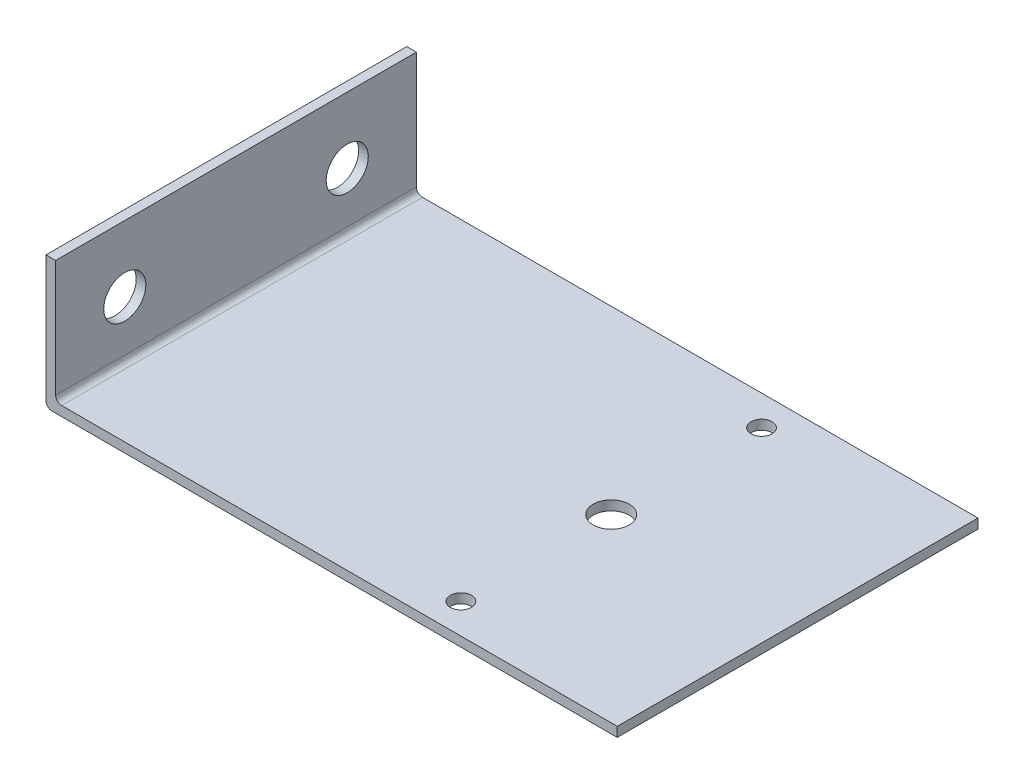
SolidWorks part; units mm, degrees
ref_plane "Piano frontale" through (0, 0, 0) normal (0, 0, 1) x (1, 0, 0)
ref_plane "Piano superiore" through (0, 0, 0) normal (0, 1, 0) x (1, 0, 0)
ref_plane "Piano destro" through (0, 0, 0) normal (1, 0, 0) x (0, 0, -1)
sketch "Schizzo1" plane through (0, 0, 0) normal (0, 0, 1) x (1, 0, 0)
  line L0 (-95, 22) -> (-95, 0)
  line L1 (-95, 0) -> (0, 0)
  line L2 (0, 0) -> (0, 1.6)
  line L3 (0, 1.6) -> (-93.4, 1.6)
  line L4 (-93.4, 1.6) -> (-93.4, 22)
  line L5 (-93.4, 22) -> (-95, 22)
  dimension "D1" = 1.6
  dimension "D2" = 1.6
  dimension "D3" = 22
  dimension "D4" = 95
extrude "Estrusione-Estrusione1" add sketch "Schizzo1" along normal blind 60
fillet "Raccordo1" radius 1 1 edges at (-95, 0, 30)
fillet "Raccordo2" radius 1 1 edges at (-93.4, 1.6, 30)
sketch "Schizzo2" plane through (0, 1.6, 0) normal (0, 1, 0) x (1, 0, 0)
  line L0 (-103.5659, -30) -> (25.6447, -30) construction
  line L1 (0, 0) -> (-92.4, 0) construction
  line L2 (0, -60) -> (-92.4, -60) construction
  line L3 (0, -60) -> (0, 0) construction
  circle A0 centre (-31, -5) radius 1.75
  circle A1 centre (-31, -30) radius 3
  circle A2 centre (-31, -55) radius 1.75
  dimension "D2" = 3.5
  dimension "D4" = 6
  dimension "D1" = 50
  dimension "D3" = 31
extrude "Taglio-Estrusione1" cut sketch "Schizzo2" against normal up to next
sketch "Schizzo3" plane through (-95, 0, 0) normal (-1, 0, 0) x (0, 0, 1)
  line L0 (0, 22) -> (0, 1) construction
  line L3 (30, 22) -> (30, 0) construction
  line L4 (60, 22) -> (0, 22) construction
  line L5 (60, 0) -> (0, 0) construction
  circle A0 centre (11.5, 11) radius 3.5
  circle A1 centre (48.5, 11) radius 3.5
  dimension "D1" = 7
  dimension "D2" = 11.5
  dimension "D3" = 11
extrude "Taglio-Estrusione2" cut sketch "Schizzo3" against normal through all
